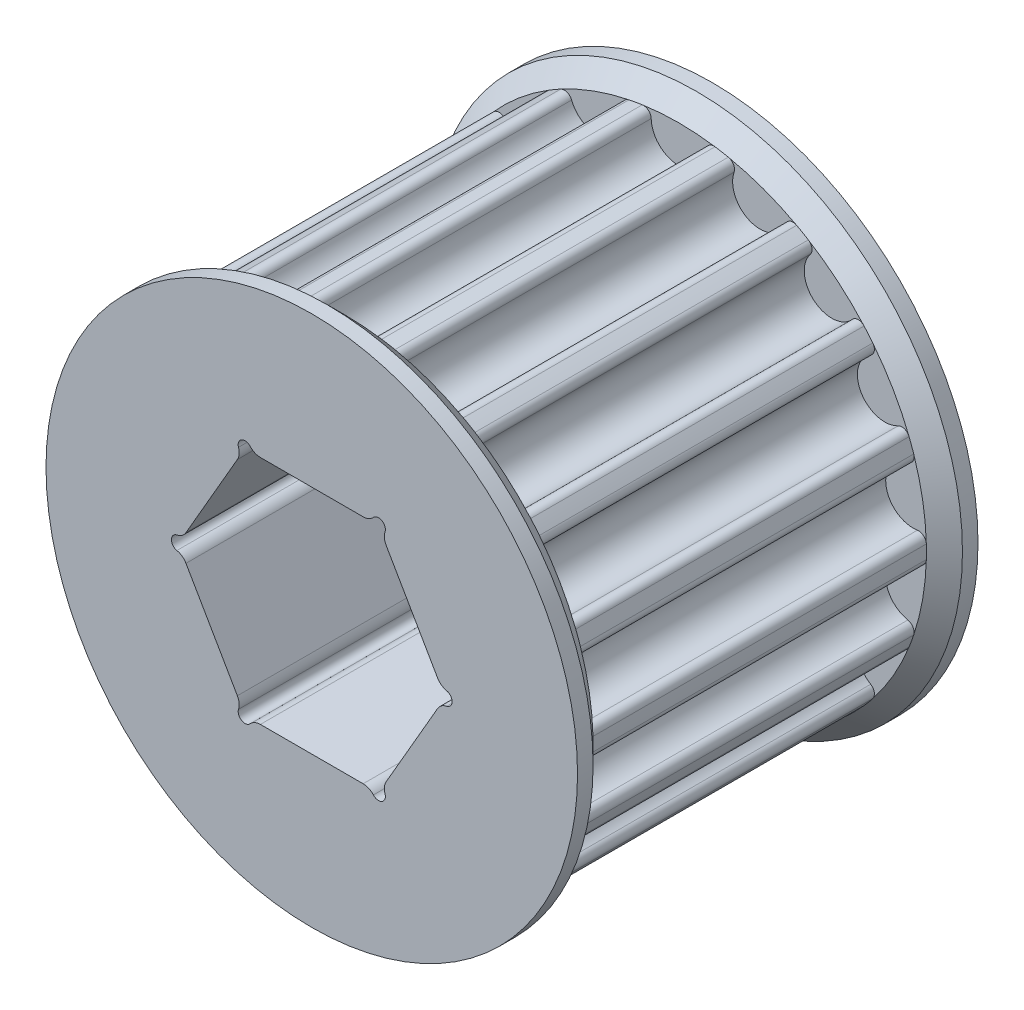
SolidWorks part; units mm, degrees
material "Nailon 6/10"
ref_plane "Alzado" through (0, 0, 0) normal (0, 0, 1) x (1, 0, 0)
ref_plane "Planta" through (0, 0, 0) normal (0, 1, 0) x (1, 0, 0)
ref_plane "Vista lateral" through (0, 0, 0) normal (1, 0, 0) x (0, 0, -1)
sketch "Croquis3" plane through (0, 0, 0) normal (0, 0, 1) x (1, 0, 0)
  line L0 (0, 0) -> (0, 13.75) construction
  line L1 (0, 0) -> (4.7028, 12.9208) construction
  circle A0 centre (0, 0) radius 13.75 construction
  circle A1 centre (0, 0) radius 11.69 construction
  circle A2 centre (0, 13.215) radius 1.525 construction
  circle A3 centre (1.9546, 13.1758) radius 0.43 construction
  circle A4 centre (4.5198, 12.418) radius 1.525 construction
  circle A5 centre (2.6697, 13.0497) radius 0.43 construction
  arc A6 (0, 11.69) -> (1.5247, 13.1844) centre (0, 13.215) ccw
  arc A7 (1.5247, 13.1844) -> (2.0177, 13.6012) centre (1.9546, 13.1758) cw
  arc A8 (2.0177, 13.6012) -> (2.7558, 13.471) centre (0, 0) cw
  arc A9 (2.7558, 13.471) -> (3.0766, 12.9108) centre (2.6697, 13.0497) cw
  arc A10 (3.0766, 12.9108) -> (3.9982, 10.985) centre (4.5198, 12.418) ccw
  arc A11 (7.3068, 11.0799) -> (7.5142, 8.9551) centre (8.4944, 10.1233) ccw
  arc A12 (7.197, 11.716) -> (7.3068, 11.0799) centre (6.9719, 11.3497) cw
  arc A13 (6.5479, 12.0908) -> (7.197, 11.716) centre (0, 0) cw
  arc A14 (5.9421, 11.8678) -> (6.5479, 12.0908) centre (6.3431, 11.7127) cw
  arc A15 (3.9982, 10.985) -> (5.9421, 11.8678) centre (4.5198, 12.418) ccw
  arc A16 (10.6557, 7.9126) -> (10.1238, 5.845) centre (11.4445, 6.6075) ccw
  arc A17 (10.7701, 8.548) -> (10.6557, 7.9126) centre (10.4333, 8.2806) cw
  arc A18 (10.2883, 9.1221) -> (10.7701, 8.548) centre (0, 0) cw
  arc A19 (9.6428, 9.1198) -> (10.2883, 9.1221) centre (9.9666, 8.8369) cw
  arc A20 (7.5142, 8.9551) -> (9.6428, 9.1198) centre (8.4944, 10.1233) ccw
  arc A21 (12.7194, 3.791) -> (11.5124, 2.0299) centre (13.0142, 2.2948) ccw
  arc A22 (13.0441, 4.3489) -> (12.7194, 3.791) centre (12.6362, 4.2129) cw
  arc A23 (12.7878, 5.0532) -> (13.0441, 4.3489) centre (0, 0) cw
  arc A24 (12.1804, 5.2718) -> (12.7878, 5.0532) centre (12.3879, 4.8952) cw
  arc A25 (10.1238, 5.845) -> (12.1804, 5.2718) centre (11.4445, 6.6075) ccw
  arc A26 (13.2489, -0.7879) -> (11.5124, -2.0299) centre (13.0142, -2.2948) ccw
  arc A27 (13.7449, -0.3748) -> (13.2489, -0.7879) centre (13.3151, -0.363) cw
  arc A28 (13.7449, 0.3748) -> (13.7449, -0.3748) centre (0, 0) cw
  arc A29 (13.2489, 0.7879) -> (13.7449, 0.3748) centre (13.3151, 0.363) cw
  arc A30 (11.5124, 2.0299) -> (13.2489, 0.7879) centre (13.0142, 2.2948) ccw
  arc A31 (12.1804, -5.2718) -> (10.1238, -5.845) centre (11.4445, -6.6075) ccw
  arc A32 (12.7878, -5.0532) -> (12.1804, -5.2718) centre (12.3879, -4.8952) cw
  arc A33 (13.0441, -4.3489) -> (12.7878, -5.0532) centre (0, 0) cw
  arc A34 (12.7194, -3.791) -> (13.0441, -4.3489) centre (12.6362, -4.2129) cw
  arc A35 (11.5124, -2.0299) -> (12.7194, -3.791) centre (13.0142, -2.2948) ccw
  arc A36 (9.6428, -9.1198) -> (7.5142, -8.9551) centre (8.4944, -10.1233) ccw
  arc A37 (10.2883, -9.1221) -> (9.6428, -9.1198) centre (9.9666, -8.8369) cw
  arc A38 (10.7701, -8.548) -> (10.2883, -9.1221) centre (0, 0) cw
  arc A39 (10.6557, -7.9126) -> (10.7701, -8.548) centre (10.4333, -8.2806) cw
  arc A40 (10.1238, -5.845) -> (10.6557, -7.9126) centre (11.4445, -6.6075) ccw
  arc A41 (5.9421, -11.8678) -> (3.9982, -10.985) centre (4.5198, -12.418) ccw
  arc A42 (6.5479, -12.0908) -> (5.9421, -11.8678) centre (6.3431, -11.7127) cw
  arc A43 (7.197, -11.716) -> (6.5479, -12.0908) centre (0, 0) cw
  arc A44 (7.3068, -11.0799) -> (7.197, -11.716) centre (6.9719, -11.3497) cw
  arc A45 (7.5142, -8.9551) -> (7.3068, -11.0799) centre (8.4944, -10.1233) ccw
  arc A46 (1.5247, -13.1844) -> (0, -11.69) centre (0, -13.215) ccw
  arc A47 (2.0177, -13.6012) -> (1.5247, -13.1844) centre (1.9546, -13.1758) cw
  arc A48 (2.7558, -13.471) -> (2.0177, -13.6012) centre (0, 0) cw
  arc A49 (3.0766, -12.9108) -> (2.7558, -13.471) centre (2.6697, -13.0497) cw
  arc A50 (3.9982, -10.985) -> (3.0766, -12.9108) centre (4.5198, -12.418) ccw
  arc A51 (-3.0766, -12.9108) -> (-3.9982, -10.985) centre (-4.5198, -12.418) ccw
  arc A52 (-2.7558, -13.471) -> (-3.0766, -12.9108) centre (-2.6697, -13.0497) cw
  arc A53 (-2.0177, -13.6012) -> (-2.7558, -13.471) centre (0, 0) cw
  arc A54 (-1.5247, -13.1844) -> (-2.0177, -13.6012) centre (-1.9546, -13.1758) cw
  arc A55 (0, -11.69) -> (-1.5247, -13.1844) centre (0, -13.215) ccw
  arc A56 (-7.3068, -11.0799) -> (-7.5142, -8.9551) centre (-8.4944, -10.1233) ccw
  arc A57 (-7.197, -11.716) -> (-7.3068, -11.0799) centre (-6.9719, -11.3497) cw
  arc A58 (-6.5479, -12.0908) -> (-7.197, -11.716) centre (0, 0) cw
  arc A59 (-5.9421, -11.8678) -> (-6.5479, -12.0908) centre (-6.3431, -11.7127) cw
  arc A60 (-3.9982, -10.985) -> (-5.9421, -11.8678) centre (-4.5198, -12.418) ccw
  arc A61 (-10.6557, -7.9126) -> (-10.1238, -5.845) centre (-11.4445, -6.6075) ccw
  arc A62 (-10.7701, -8.548) -> (-10.6557, -7.9126) centre (-10.4333, -8.2806) cw
  arc A63 (-10.2883, -9.1221) -> (-10.7701, -8.548) centre (0, 0) cw
  arc A64 (-9.6428, -9.1198) -> (-10.2883, -9.1221) centre (-9.9666, -8.8369) cw
  arc A65 (-7.5142, -8.9551) -> (-9.6428, -9.1198) centre (-8.4944, -10.1233) ccw
  arc A66 (-12.7194, -3.791) -> (-11.5124, -2.0299) centre (-13.0142, -2.2948) ccw
  arc A67 (-13.0441, -4.3489) -> (-12.7194, -3.791) centre (-12.6362, -4.2129) cw
  arc A68 (-12.7878, -5.0532) -> (-13.0441, -4.3489) centre (0, 0) cw
  arc A69 (-12.1804, -5.2718) -> (-12.7878, -5.0532) centre (-12.3879, -4.8952) cw
  arc A70 (-10.1238, -5.845) -> (-12.1804, -5.2718) centre (-11.4445, -6.6075) ccw
  arc A71 (-13.2489, 0.7879) -> (-11.5124, 2.0299) centre (-13.0142, 2.2948) ccw
  arc A72 (-13.7449, 0.3748) -> (-13.2489, 0.7879) centre (-13.3151, 0.363) cw
  arc A73 (-13.7449, -0.3748) -> (-13.7449, 0.3748) centre (0, 0) cw
  arc A74 (-13.2489, -0.7879) -> (-13.7449, -0.3748) centre (-13.3151, -0.363) cw
  arc A75 (-11.5124, -2.0299) -> (-13.2489, -0.7879) centre (-13.0142, -2.2948) ccw
  arc A76 (-12.1804, 5.2718) -> (-10.1238, 5.845) centre (-11.4445, 6.6075) ccw
  arc A77 (-12.7878, 5.0532) -> (-12.1804, 5.2718) centre (-12.3879, 4.8952) cw
  arc A78 (-13.0441, 4.3489) -> (-12.7878, 5.0532) centre (0, 0) cw
  arc A79 (-12.7194, 3.791) -> (-13.0441, 4.3489) centre (-12.6362, 4.2129) cw
  arc A80 (-11.5124, 2.0299) -> (-12.7194, 3.791) centre (-13.0142, 2.2948) ccw
  arc A81 (-9.6428, 9.1198) -> (-7.5142, 8.9551) centre (-8.4944, 10.1233) ccw
  arc A82 (-10.2883, 9.1221) -> (-9.6428, 9.1198) centre (-9.9666, 8.8369) cw
  arc A83 (-10.7701, 8.548) -> (-10.2883, 9.1221) centre (0, 0) cw
  arc A84 (-10.6557, 7.9126) -> (-10.7701, 8.548) centre (-10.4333, 8.2806) cw
  arc A85 (-10.1238, 5.845) -> (-10.6557, 7.9126) centre (-11.4445, 6.6075) ccw
  arc A86 (-5.9421, 11.8678) -> (-3.9982, 10.985) centre (-4.5198, 12.418) ccw
  arc A87 (-6.5479, 12.0908) -> (-5.9421, 11.8678) centre (-6.3431, 11.7127) cw
  arc A88 (-7.197, 11.716) -> (-6.5479, 12.0908) centre (0, 0) cw
  arc A89 (-7.3068, 11.0799) -> (-7.197, 11.716) centre (-6.9719, 11.3497) cw
  arc A90 (-7.5142, 8.9551) -> (-7.3068, 11.0799) centre (-8.4944, 10.1233) ccw
  arc A91 (-1.5247, 13.1844) -> (0, 11.69) centre (0, 13.215) ccw
  arc A92 (-2.0177, 13.6012) -> (-1.5247, 13.1844) centre (-1.9546, 13.1758) cw
  arc A93 (-2.7558, 13.471) -> (-2.0177, 13.6012) centre (0, 0) cw
  arc A94 (-3.0766, 12.9108) -> (-2.7558, 13.471) centre (-2.6697, 13.0497) cw
  arc A95 (-3.9982, 10.985) -> (-3.0766, 12.9108) centre (-4.5198, 12.418) ccw
  dimension "D1" = 27.5
  dimension "D2" = 23.38
  dimension "D3" = 3.05
  dimension "D4" = 0.86
  dimension "D5" = 20
  dimension "D6" = 18
extrude "Saliente-Extruir1" add sketch "Croquis3" along normal mid plane 18.5 contours A65 A56 A57 A58 A59 A60 A51 A52 A53 A54 A55 A46 A47 A48 A49 A50 A41 A42 A43 A44 A45 A36 A37 A38 A39 A40 A31 A32 A33 A34 A35 A26 A27 A28 A29 A30 A21 A22 A23 A24 A25 A16 A17 A18 A19 A20 A11 A12 A13 A14 A15
sketch "Croquis5" plane through (0, 0, 9.25) normal (0, 0, 1) x (1, 0, 0)
  circle A0 centre (0, 0) radius 13.75
  arc A1 (2.7558, 13.471) -> (2.0177, 13.6012) centre (0, 0) ccw construction
extrude "Saliente-Extruir2" add sketch "Croquis5" along normal blind 1 draft 45 draft outward yes
sketch "Croquis7" plane through (0, 0, 10.25) normal (0, 0, 1) x (1, 0, 0)
  circle A0 centre (0, 0) radius 14.75 construction
  circle A1 centre (0, 0) radius 14.75
extrude "Saliente-Extruir3" add sketch "Croquis7" along normal blind 0.8625
mirror "Simetría1" about plane through (0, 0, 0) normal (0, 0, 1) of "Saliente-Extruir3", "Saliente-Extruir2"
sketch "Croquis6" plane through (0, 0, 11.1125) normal (0, 0, 1) x (1, 0, 0)
  line L5 (3.7037, -6.415) -> (7.4074, 0)
  line L6 (7.4074, 0) -> (3.7037, 6.415)
  line L7 (3.7037, 6.415) -> (-3.7037, 6.415)
  line L8 (-3.7037, 6.415) -> (-7.4074, 0)
  line L9 (-7.4074, 0) -> (-3.7037, -6.415)
  line L10 (-3.7037, -6.415) -> (3.7037, -6.415)
  circle A1 centre (0, 0) radius 6.415 construction
  arc A2 (-3.3227, 6.415) -> (-3.8942, 6.085) centre (-3.7037, 6.415) ccw
  arc A3 (3.8942, 6.085) -> (3.3227, 6.415) centre (3.7037, 6.415) ccw
  arc A4 (7.2169, -0.33) -> (7.2169, 0.33) centre (7.4074, 0) ccw
  arc A5 (3.3227, -6.415) -> (3.8942, -6.085) centre (3.7037, -6.415) ccw
  arc A6 (-3.8942, -6.085) -> (-3.3227, -6.415) centre (-3.7037, -6.415) ccw
  arc A7 (-7.2169, 0.33) -> (-7.2169, -0.33) centre (-7.4074, 0) ccw
  point P11 (0, 0)
  dimension "D1" = 12.83
  dimension "D2" = 0.381
  dimension "D3" = 6
extrude "Cortar-Extruir1" cut sketch "Croquis6" against normal through all contours L9 L10 L5 L6 L7 L8 | L5 A4 L6 | L6 A3 L7 | L7 A2 L8 | L8 A7 L9 | L9 A6 L10 | L10 A5 L5
fillet "Redondeo1" radius 0.762 12 edges at (3.8942, 6.085, 0) (3.3227, 6.415, 0) (7.2169, -0.33, 0) (7.2169, 0.33, 0) (-3.8942, -6.085, 0) (-3.3227, -6.415, 0) (3.3227, -6.415, 0) (3.8942, -6.085, 0) (-7.2169, -0.33, 0) (-7.2169, 0.33, 0) (-3.8942, 6.085, 0) (-3.3227, 6.415, 0)
equation "\"X\"= 27.5"
equation "\"N\"= 18"
equation "\"D1@Croquis3\"=\"X\""
equation "\"Y\"= \"X\" - 2 * 2.06"
equation "\"A\"= 360 / \"N\""
equation "\"D2@Croquis3\"=\"Y\""
equation "\"D5@Croquis3\"=\"A\""
equation "\"D6@Croquis3\"=\"N\""
